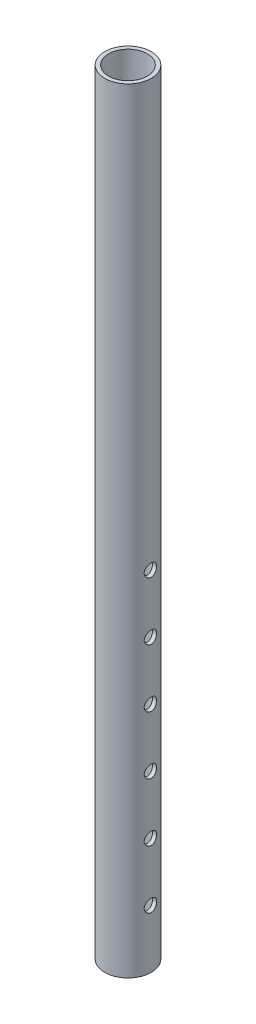
SolidWorks part; units mm, degrees
material "Hexcel AS4C (3000 丝)"
ref_plane "前视基准面" through (0, 0, 0) normal (0, 0, 1) x (1, 0, 0)
ref_plane "上视基准面" through (0, 0, 0) normal (0, 1, 0) x (1, 0, 0)
ref_plane "右视基准面" through (0, 0, 0) normal (1, 0, 0) x (0, 0, -1)
sketch "草图1" plane through (0, 0, 0) normal (0, 1, 0) x (1, 0, 0)
  circle A0 centre (0, 0) radius 5
  circle A1 centre (0, 0) radius 6
  dimension "D1" = 12
  dimension "D2" = 10
extrude "凸台-拉伸1" add sketch "草图1" along normal blind 200
sketch "草图4" plane through (0, 0, 0) normal (1, 0, 0) x (0, 0, -1)
  line L0 (0, 0) -> (0, 71.3507) construction
  line L1 (-6, 0) -> (6, 0) construction
  circle A0 centre (0, 15) radius 1.6
  dimension "D1" = 3.2
  dimension "D2" = 15
extrude "切除-拉伸2" cut sketch "草图4" against normal through all both and the other way through all
pattern_linear "阵列(线性)1" count 6 spacing 15 along (0, 1, 0) of "切除-拉伸2"
